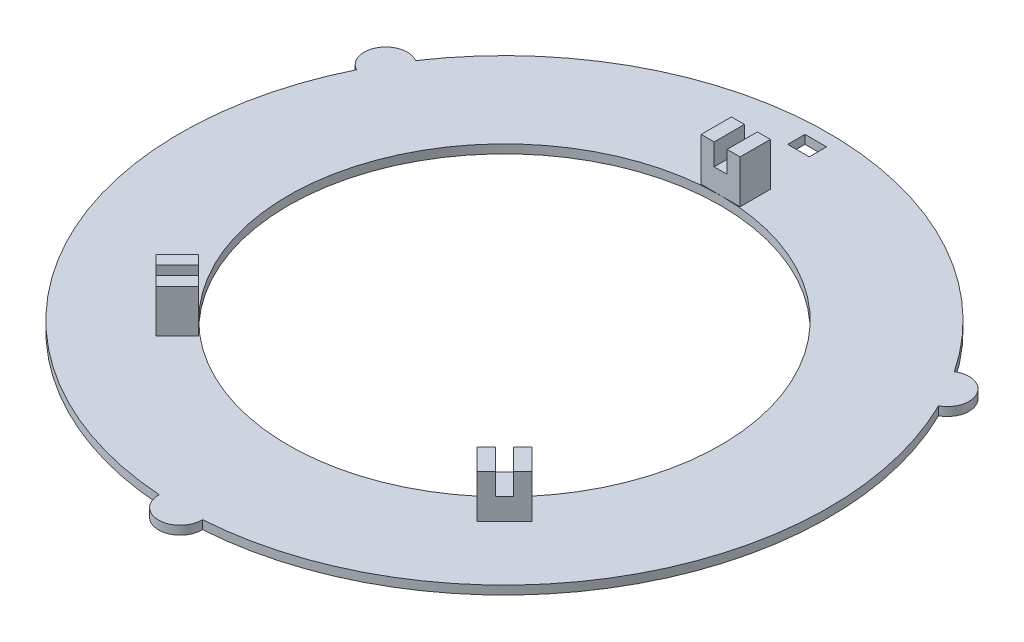
SolidWorks part; units mm, degrees
ref_plane "前视基准面" through (0, 0, 0) normal (0, 0, 1) x (1, 0, 0)
ref_plane "上视基准面" through (0, 0, 0) normal (0, 1, 0) x (1, 0, 0)
ref_plane "右视基准面" through (0, 0, 0) normal (1, 0, 0) x (0, 0, -1)
sketch "Sketch1" plane through (0, 0, 0) normal (0, 1, 0) x (1, 0, 0)
  circle A0 centre (0, 0) radius 75
  circle A1 centre (0, 0) radius 50
  dimension "D1" = 150
  dimension "D2" = 100
extrude "Boss-Extrude1" add sketch "Sketch1" along normal blind 2
sketch "Sketch2" plane through (0, 2, 0) normal (0, 1, 0) x (1, 0, 0)
  line L0 (0, 0) -> (0, 70) construction
  line L1 (0, 70) -> (0, 75) construction
  line L2 (-2.5, 68) -> (2.5, 68)
  line L3 (-2.5, 68) -> (-2.5, 72)
  line L4 (-2.5, 72) -> (2.5, 72)
  line L5 (2.5, 68) -> (2.5, 72)
  line L6 (-2.5, 68) -> (2.5, 72) construction
  line L7 (-2.5, 72) -> (2.5, 68) construction
  circle A0 centre (0, 0) radius 75 construction
  dimension "D1" = 5
  dimension "D2" = 4
  dimension "D3" = 70
extrude "Cut-Extrude1" cut sketch "Sketch2" against normal up to next
sketch "Sketch4" plane through (0, 2, 0) normal (0, 1, 0) x (1, 0, 0)
  line L0 (0, 0) -> (75, 0) construction
  line L1 (0, 0) -> (0, 75) construction
  line L2 (0, 50) -> (1.5, 50) construction
  line L3 (1.5, 50) -> (1.5, 57)
  line L4 (1.5, 57) -> (4.5, 57)
  line L5 (4.5, 57) -> (4.5, 50)
  line L6 (4.5, 50) -> (1.5, 50)
  line L7 (-4.5, 57) -> (-4.5, 50)
  line L8 (-4.5, 50) -> (-1.5, 50)
  line L9 (-1.5, 50) -> (-1.5, 57)
  line L10 (-1.5, 57) -> (-4.5, 57)
  circle A0 centre (0, 0) radius 75 construction
  dimension "D1" = 1.5
  dimension "D2" = 3
  dimension "D3" = 7
  dimension "D4" = 90
  dimension "D5" = 25
extrude "Boss-Extrude2" add sketch "Sketch4" along normal blind 10
sketch "Sketch5" plane through (0, 2, 0) normal (0, 1, 0) x (1, 0, 0)
  line L0 (-1.5, 50) -> (-1.5, 57)
  line L1 (-1.5, 57) -> (1.5, 57)
  line L2 (4.5, 57) -> (1.5, 57) construction
  line L3 (1.5, 57) -> (1.5, 50) construction
  line L4 (1.5, 57) -> (1.5, 50)
  line L5 (1.5, 57) -> (1.5, 50) construction
  line L6 (1.5, 50) -> (-1.5, 50)
extrude "Boss-Extrude3" add sketch "Sketch5" along normal blind 5
pattern_circular "CirPattern1" count 2 every 135 about axis through (0, 2, 0) along (0, 1, 0) of "Boss-Extrude2", "Boss-Extrude3"
pattern_circular "CirPattern2" count 2 every 135 about axis through (0, 0, 0) along (0, 1, 0) of "Boss-Extrude2", "Boss-Extrude3"
sketch "Sketch6" plane through (0, 0, 0) normal (0, -1, 0) x (1, 0, 0)
  line L0 (0, 0) -> (64.9519, -37.5) construction
  line L1 (0, 0) -> (75, 0) construction
  circle A0 centre (64.9519, -37.5) radius 5
  circle A1 centre (0, 0) radius 75 construction
  dimension "D1" = 10
  dimension "D2" = 30
extrude "Boss-Extrude4" add sketch "Sketch6" against normal up to surface (2 mm away) up to face at (0, 2, 75)
pattern_circular "CirPattern3" count 3 over 360 about axis through (0, 0, 0) along (0, 1, 0) of "Boss-Extrude4"
